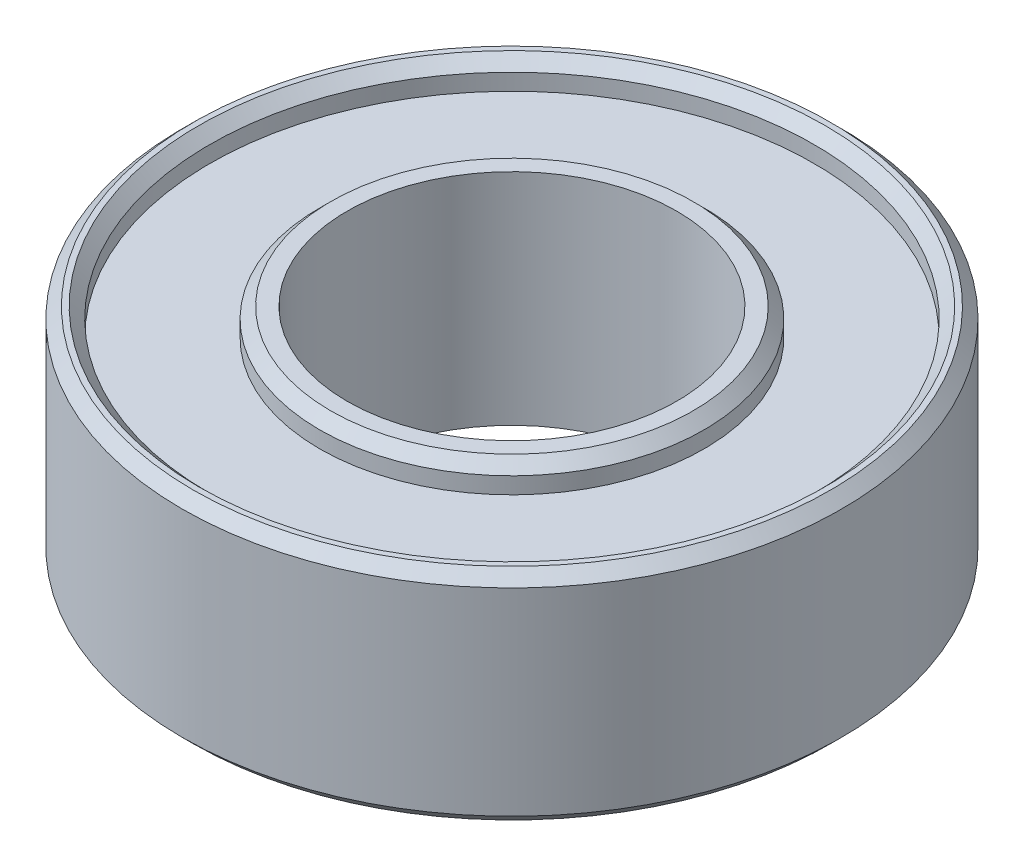
SolidWorks part; units mm, degrees
ref_plane "前视基准面" through (0, 0, 0) normal (0, 0, 1) x (1, 0, 0)
ref_plane "上视基准面" through (0, 0, 0) normal (0, 1, 0) x (1, 0, 0)
ref_plane "右视基准面" through (0, 0, 0) normal (1, 0, 0) x (0, 0, -1)
other "Configuration Table"
sketch "草图1" plane through (0, 0, 0) normal (0, 1, 0) x (1, 0, 0)
  circle A0 centre (0, 0) radius 3
  dimension "D1" = 6
extrude "凸台-拉伸1" add sketch "草图1" along normal blind 2
sketch "草图2" plane through (0, 0, 0) normal (0, 1, 0) x (1, 0, 0)
  circle A0 centre (0, 0) radius 1.5
  dimension "D1" = 3
extrude "切除-拉伸1" cut sketch "草图2" along normal up to surface (2 mm away) up to face at (0, 2, 3)
sketch "草图3" plane through (0, 0, 0) normal (0, 1, 0) x (1, 0, 0)
  circle A0 centre (0, 0) radius 2.75
  circle A1 centre (0, 0) radius 1.75
  dimension "D1" = 5.5
  dimension "D2" = 3.5
extrude "切除-拉伸2" cut sketch "草图3" against normal blind 0.25 from surface at 2 starting at face at (0, 2, 1.5)
sketch "草图4" plane through (0, 0, 0) normal (0, 1, 0) x (1, 0, 0)
  circle A0 centre (0, 0) radius 1.75 construction
  circle A1 centre (0, 0) radius 2.75
  circle A2 centre (0, 0) radius 2.75
  circle A3 centre (0, 0) radius 1.75
  dimension "D1" = 0
extrude "切除-拉伸3" cut sketch "草图4" along normal blind 0.25
chamfer "倒角1" distance 0.1 angle 45 6 edges at (0, 2, 1.75) (0, 0, 1.75) (0, 0, 2.75) (0, 0, 3) (0, 2, 3) (0, 2, 2.75)
